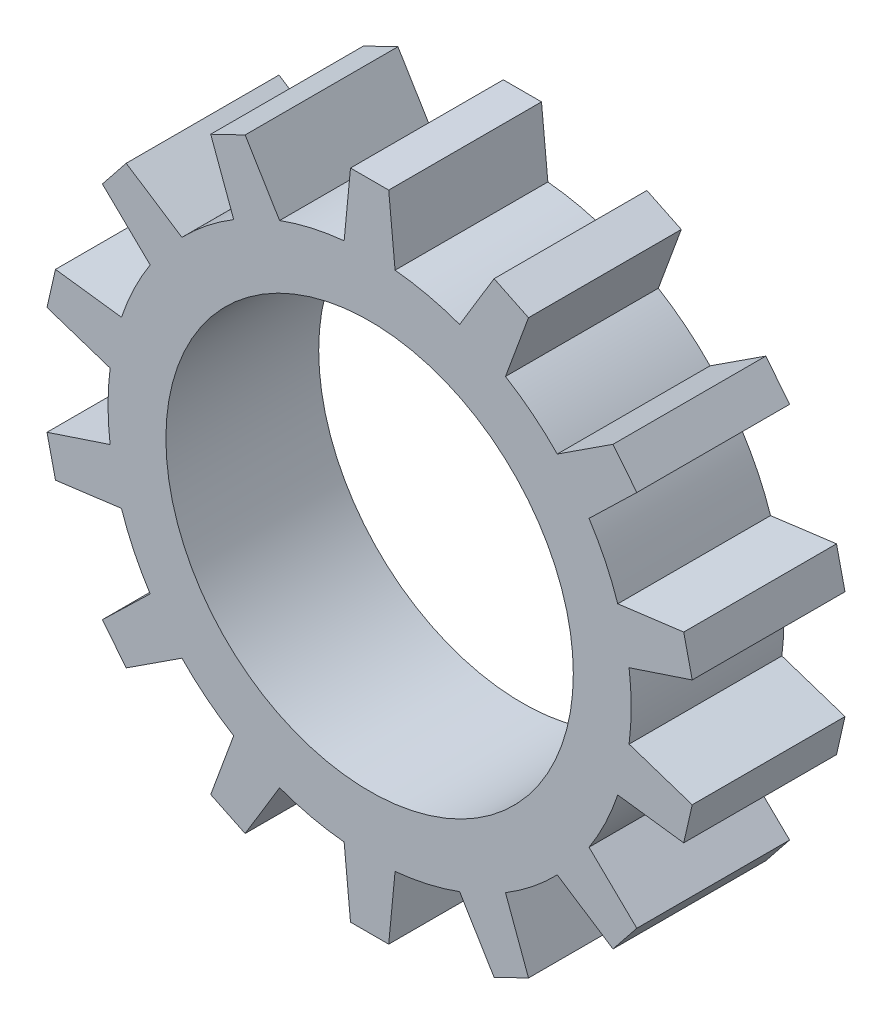
SolidWorks part; units mm, degrees
ref_plane "Alzado" through (0, 0, 0) normal (0, 0, 1) x (1, 0, 0)
ref_plane "Planta" through (0, 0, 0) normal (0, 1, 0) x (1, 0, 0)
ref_plane "Vista lateral" through (0, 0, 0) normal (1, 0, 0) x (0, 0, -1)
sketch "Croquis1" plane through (0, 0, 0) normal (0, 0, 1) x (1, 0, 0)
  line L0 (0, -0.8594) -> (0, 1.437) construction
  line L1 (-0.5, 5.1117) -> (-0.375, 6.4117)
  line L2 (-0.375, 6.4117) -> (0.375, 6.4117)
  line L3 (0.375, 6.4117) -> (0.5, 5.1117)
  line L4 (2.4441, 5.9395) -> (3.1198, 5.6141)
  line L5 (3.1198, 5.6141) -> (2.6684, 4.3886)
  line L6 (1.7674, 4.8224) -> (2.4441, 5.9395)
  line L7 (4.7791, 4.2908) -> (5.2467, 3.7045)
  line L8 (5.2467, 3.7045) -> (4.3082, 2.7962)
  line L9 (3.6848, 3.578) -> (4.7791, 4.2908)
  line L10 (6.1675, 1.7923) -> (6.3344, 1.0611)
  line L11 (6.3344, 1.0611) -> (5.0948, 0.65)
  line L12 (4.8723, 1.6249) -> (6.1675, 1.7923)
  line L13 (6.3344, -1.0611) -> (6.1675, -1.7923)
  line L14 (6.1675, -1.7923) -> (4.8723, -1.6249)
  line L15 (5.0948, -0.65) -> (6.3344, -1.0611)
  line L16 (5.2467, -3.7045) -> (4.7791, -4.2908)
  line L17 (4.7791, -4.2908) -> (3.6848, -3.578)
  line L18 (4.3082, -2.7962) -> (5.2467, -3.7045)
  line L19 (3.1198, -5.6141) -> (2.4441, -5.9395)
  line L20 (2.4441, -5.9395) -> (1.7674, -4.8224)
  line L21 (2.6684, -4.3886) -> (3.1198, -5.6141)
  line L22 (0.375, -6.4117) -> (-0.375, -6.4117)
  line L23 (-0.375, -6.4117) -> (-0.5, -5.1117)
  line L24 (0.5, -5.1117) -> (0.375, -6.4117)
  line L25 (-2.4441, -5.9395) -> (-3.1198, -5.6141)
  line L26 (-3.1198, -5.6141) -> (-2.6684, -4.3886)
  line L27 (-1.7674, -4.8224) -> (-2.4441, -5.9395)
  line L28 (-4.7791, -4.2908) -> (-5.2467, -3.7045)
  line L29 (-5.2467, -3.7045) -> (-4.3082, -2.7962)
  line L30 (-3.6848, -3.578) -> (-4.7791, -4.2908)
  line L31 (-6.1675, -1.7923) -> (-6.3344, -1.0611)
  line L32 (-6.3344, -1.0611) -> (-5.0948, -0.65)
  line L33 (-4.8723, -1.6249) -> (-6.1675, -1.7923)
  line L34 (-6.3344, 1.0611) -> (-6.1675, 1.7923)
  line L35 (-6.1675, 1.7923) -> (-4.8723, 1.6249)
  line L36 (-5.0948, 0.65) -> (-6.3344, 1.0611)
  line L37 (-5.2467, 3.7045) -> (-4.7791, 4.2908)
  line L38 (-4.7791, 4.2908) -> (-3.6848, 3.578)
  line L39 (-4.3082, 2.7962) -> (-5.2467, 3.7045)
  line L40 (-3.1198, 5.6141) -> (-2.4441, 5.9395)
  line L41 (-2.4441, 5.9395) -> (-1.7674, 4.8224)
  line L42 (-2.6684, 4.3886) -> (-3.1198, 5.6141)
  arc A0 (-4.3082, 2.7962) -> (-4.8723, 1.6249) centre (0, 0) ccw
  circle A1 centre (0, 0) radius 4
  arc A2 (-5.0948, 0.65) -> (-5.0948, -0.65) centre (0, 0) ccw
  arc A3 (-4.8723, -1.6249) -> (-4.3082, -2.7962) centre (0, 0) ccw
  arc A4 (-3.6848, -3.578) -> (-2.6684, -4.3886) centre (0, 0) ccw
  arc A5 (-1.7674, -4.8224) -> (-0.5, -5.1117) centre (0, 0) ccw
  arc A6 (0.5, -5.1117) -> (1.7674, -4.8224) centre (0, 0) ccw
  arc A7 (2.6684, -4.3886) -> (3.6848, -3.578) centre (0, 0) ccw
  arc A8 (4.3082, -2.7962) -> (4.8723, -1.6249) centre (0, 0) ccw
  arc A9 (5.0948, -0.65) -> (5.0948, 0.65) centre (0, 0) ccw
  arc A10 (4.8723, 1.6249) -> (4.3082, 2.7962) centre (0, 0) ccw
  arc A11 (3.6848, 3.578) -> (2.6684, 4.3886) centre (0, 0) ccw
  arc A12 (1.7674, 4.8224) -> (0.5, 5.1117) centre (0, 0) ccw
  arc A13 (-2.6684, 4.3886) -> (-3.6848, 3.578) centre (0, 0) ccw
  arc A14 (-0.5, 5.1117) -> (-1.7674, 4.8224) centre (0, 0) ccw
  point P10 (0, 0)
  point P11 (2.6164, 3.5906)
  dimension "D5" = 8
  dimension "D1" = 1
  dimension "D2" = 0.75
  dimension "D3" = 1.3
  dimension "D6" = 1.3
  dimension "D4" = 14
extrude "Saliente-Extruir1" add sketch "Croquis1" along normal blind 3
